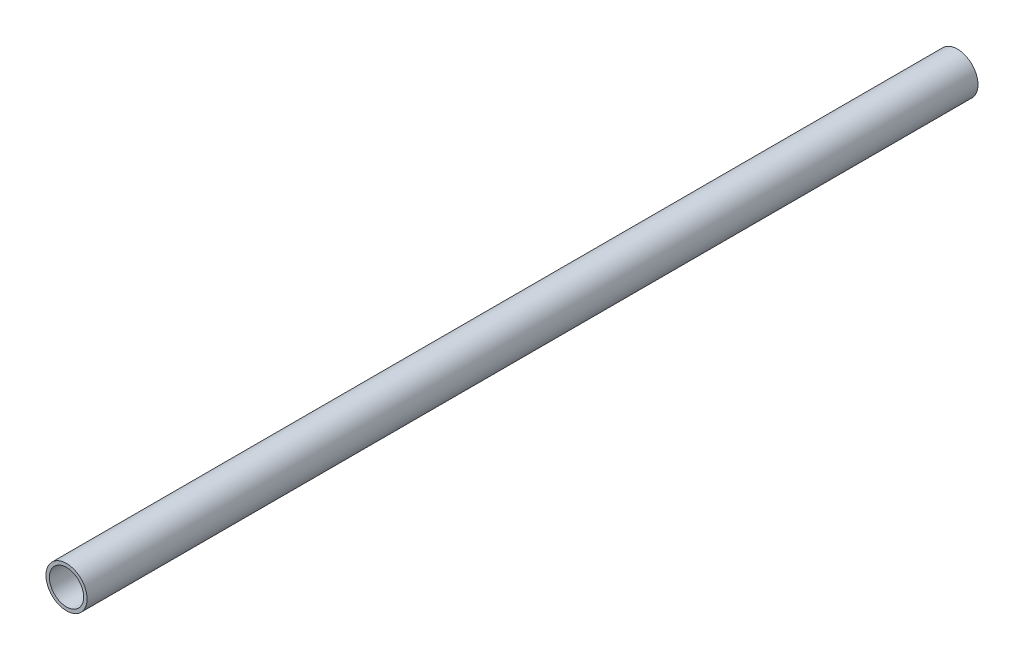
SolidWorks part; units mm, degrees
material "Alliage 1060"
ref_plane "Plan de face" through (0, 0, 0) normal (0, 0, 1) x (1, 0, 0)
ref_plane "Plan de dessus" through (0, 0, 0) normal (0, 1, 0) x (1, 0, 0)
ref_plane "Plan de droite" through (0, 0, 0) normal (1, 0, 0) x (0, 0, -1)
sketch "Esquisse1" plane through (0, 0, 0) normal (0, 0, 1) x (1, 0, 0)
  circle A0 centre (0, 0) radius 12
  circle A1 centre (0, 0) radius 10
  dimension "D1" = 24
  dimension "D2" = 2
extrude "Boss.-Extru.1" add sketch "Esquisse1" along normal blind 520
